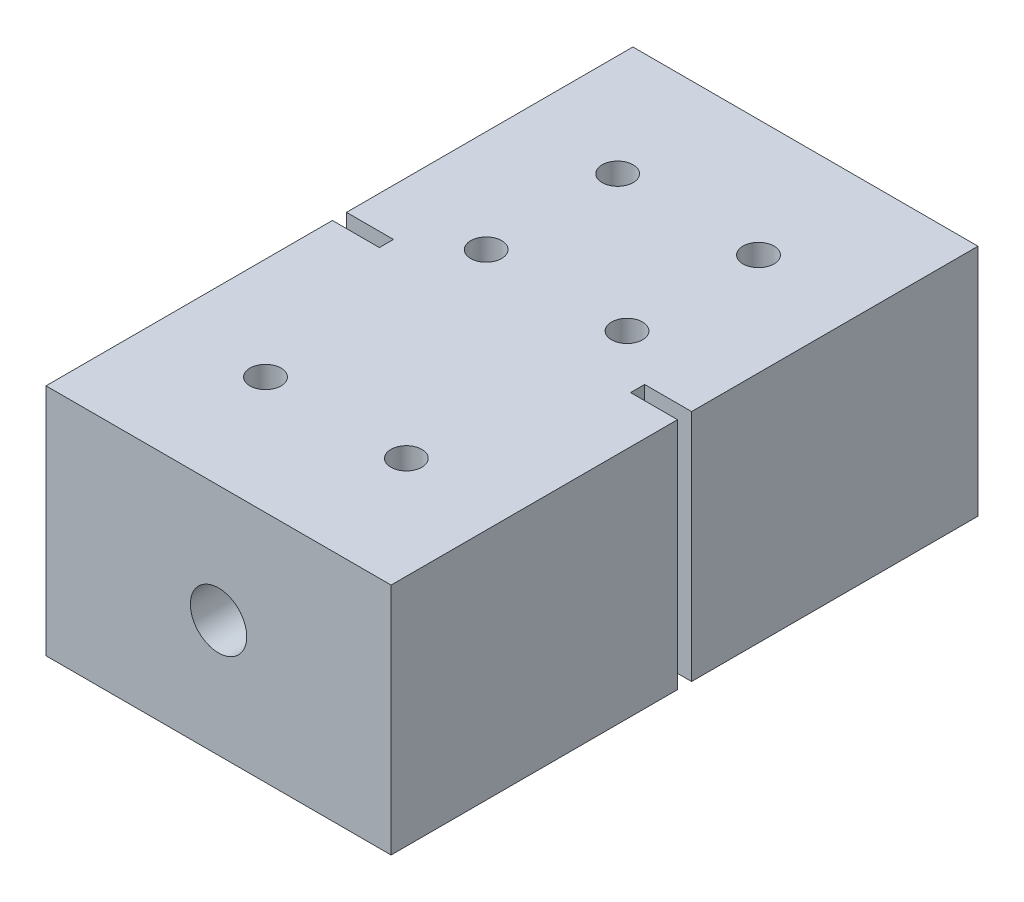
SolidWorks part; units mm, degrees
material "Beech"
ref_plane "Front Plane" through (0, 0, 0) normal (0, 0, 1) x (1, 0, 0)
ref_plane "Top Plane" through (0, 0, 0) normal (0, 1, 0) x (1, 0, 0)
ref_plane "Right Plane" through (0, 0, 0) normal (1, 0, 0) x (0, 0, -1)
sketch "Sketch1" plane through (0, 0, 0) normal (0, 0, 1) x (1, 0, 0)
  line L1 (0, 0) -> (73.5, 0)
  line L2 (0, 0) -> (0, 49.8)
  line L3 (0, 49.8) -> (73.5, 49.8)
  line L4 (73.5, 0) -> (73.5, 49.8)
  dimension "D1" = 73.5
  dimension "D2" = 49.8
extrude "slider body" add sketch "Sketch1" along normal blind 125
sketch "Sketch2" plane through (0, 0, 0) normal (0, 0, -1) x (-1, 0, 0)
  line L0 (-73.5, 49.8) -> (0, 0) construction
  line L1 (-73.5, 0) -> (0, 49.8) construction
  circle A0 centre (-36.75, 24.9) radius 10.95
  dimension "D1" = 21.9
extrude "lead nut inset" cut sketch "Sketch2" against normal blind 15
sketch "Sketch3" plane through (0, 0, 15) normal (0, 0, -1) x (-1, 0, 0)
  circle A0 centre (-36.75, 24.9) radius 6
  circle A1 centre (-36.75, 24.9) radius 10.95 construction
  dimension "D1" = 12
extrude "leadscrew clearance" cut sketch "Sketch3" against normal through all
sketch "Sketch9" plane through (0, 0, 0) normal (0, -1, 0) x (1, 0, 0)
  line L0 (73.5, 125) -> (73.5, 0) construction
  line L1 (73.5, 64) -> (63.5, 64)
  line L2 (73.5, 64) -> (73.5, 61)
  line L3 (73.5, 61) -> (63.5, 61)
  line L4 (63.5, 64) -> (63.5, 61)
  point P6 (73.5, 62.5)
  point P7 (73.5, 62.5)
  dimension "D1" = 10
  dimension "D2" = 3
extrude "decoupling slit" cut sketch "Sketch9" against normal through all
hole_wizard "bolt clearance holes" positions "Sketch4" profile "Sketch6" hole size "M6" standard "ANSI Metric" end condition through all
sketch "Sketch4" plane through (0, 49.8, 0) normal (0, 1, 0) x (1, 0, 0)
  line L1 (51.75, -100) -> (21.75, -100)
  line L2 (51.75, -100) -> (51.75, -25)
  line L3 (51.75, -25) -> (21.75, -25)
  line L4 (21.75, -100) -> (21.75, -25)
  line L10 (21.75, -62.5) -> (0, -62.5)
  line L11 (0, -125) -> (0, 0) construction
  line L13 (36.75, -100) -> (36.75, -125)
  line L14 (73.5, -125) -> (0, -125) construction
  point P1 (51.75, -100)
  point P2 (21.75, -25)
  point P47 (51.75, -25)
  point P48 (21.75, -100)
  point P72 (21.75, -53)
  point P74 (51.75, -53)
  dimension "D1" = 30
  dimension "D2" = 75
  dimension "D3" = 28
sketch "Sketch6" plane through (51.75, 49.8, 100) normal (1, 0, 0) x (0, 0, 1)
  line L0 (0, 0) -> (0, 49.8)
  line L1 (0, 49.8) -> (3.3, 49.8)
  line L2 (3.3, 49.8) -> (3.3, 0)
  line L5 (3.3, 0) -> (0, 0)
  line L11 (0, -6.35) -> (0, 107.95) construction
  dimension "Thru Hole Dia." = 6.6
  dimension "Thru Hole Depth" = 49.8
sketch "Sketch7" plane through (0, 0, 0) normal (0, -1, 0) x (1, 0, 0)
  circle A0 centre (21.75, 100) radius 6
  circle A1 centre (51.75, 100) radius 6
  circle A2 centre (51.75, 25) radius 6
  circle A3 centre (21.75, 25) radius 6
  dimension "D1" = 12
extrude "nut clearance counterbores" [suppressed] cut sketch "Sketch7" against normal blind 10
ref_plane "midplane along length" through (36.75, 0, 0) normal (-1, 0, 0) x (0, 0, 1)
mirror "mirror slit" about plane through (36.75, 0, 0) normal (-1, 0, 0) of "decoupling slit"
sketch "Sketch10" plane through (0, 0, 0) normal (0, -1, 0) x (1, 0, 0)
  line L0 (73.5, 64) -> (63.5, 64) construction
  line L1 (73.5, 125) -> (70.65, 125)
  line L2 (73.5, 125) -> (73.5, 64)
  line L3 (73.5, 64) -> (70.65, 64)
  line L4 (70.65, 125) -> (70.65, 64)
  line L5 (0, 0) -> (73.5, 0) construction
  line L6 (0, 61) -> (2.85, 61)
  line L7 (0, 61) -> (0, 0)
  line L8 (0, 0) -> (2.85, 0)
  line L9 (2.85, 61) -> (2.85, 0)
  dimension "D1" = 2.85
extrude "neoprene inlay" [suppressed] cut sketch "Sketch10" against normal through all
equation "\"board_thickness\" = 18mm"
equation "\"way_width\"= 75mm"
equation "\"way_thickness\"= 50mm"
equation "\"radial_clearance\"= 0.1mm"
equation "\"slider_width\"= \"way_width\"-2* \"radial_clearance\" - 2*0.65"
equation "\"slider_thickness\" = \"way_thickness\" - 2 * \"radial_clearance\""
equation "\"column_width\"= \"way_width\" + 2 * \"board_thickness\""
equation "\"boxway_slot_width\" = 50mm"
equation "\"keeper_rail_width\" = (\"column_width\" - \"boxway_slot_width\")/2"
equation "\"slider_length\" = 125mm"
equation "\"D1@Sketch1\"=\"slider_width\""
equation "\"D2@Sketch1\"=\"slider_thickness\""
equation "\"D1@slider body\" = \"slider_length\""
equation "\"nut_diameter\"= 22mm"
equation "\"nut_length\"= 15mm"
equation "\"D1@Sketch2\"=\"nut_diameter\"-0.1"
equation "\"D1@lead nut inset\" = \"nut_length\""
equation "\"leadscrew_diameter\"= 10mm"
equation "\"leadscrew_radial_clearance\"= 1mm"
equation "\"D1@Sketch3\"=\"leadscrew_diameter\"+2* \"leadscrew_radial_clearance\""
equation "\"bearing_bolt_pattern_width\" = 30mm"
equation "\"bearing_bolt_pattern_height\" = 75mm"
equation "\"desktop_bolt_pattern_width\" = 30mm"
equation "\"desktop_bolt_pattern_height\" = 30mm"
equation "\"D1@Sketch4\"=\"bearing_bolt_pattern_width\""
equation "\"D2@Sketch4\"=\"bearing_bolt_pattern_height\""
equation "\"bearing_bolt_nut_counterbore_diameter\" = 12mm"
equation "\"bearing_bolt_nut_counterbore_depth\"= 10mm"
equation "\"D1@Sketch7\"=\"bearing_bolt_nut_counterbore_diameter\""
equation "\"D1@nut clearance counterbores\" = \"bearing_bolt_nut_counterbore_depth\""
equation "\"D1@Sketch10\"=3.5-0.65"
